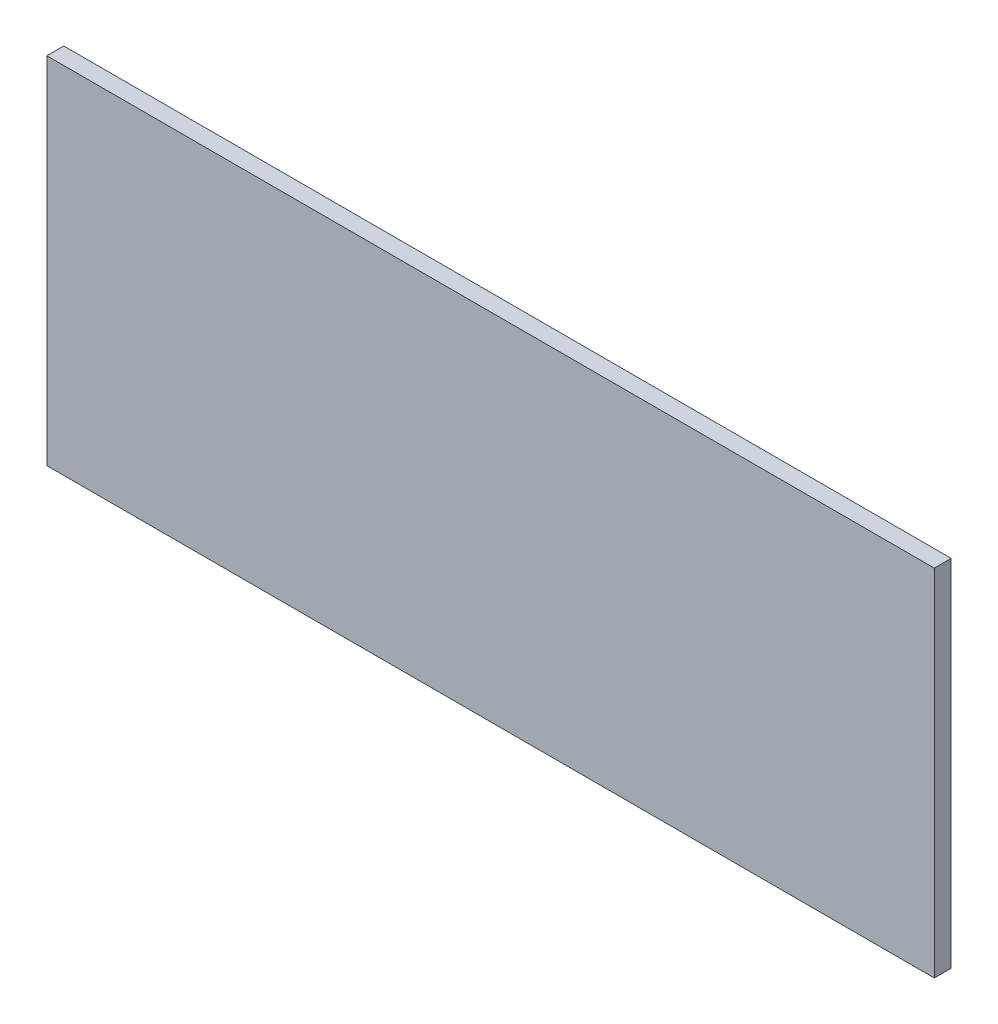
SolidWorks part; units mm, degrees
ref_plane "Alzado" through (0, 0, 0) normal (0, 0, 1) x (1, 0, 0)
ref_plane "Planta" through (0, 0, 0) normal (0, 1, 0) x (1, 0, 0)
ref_plane "Vista lateral" through (0, 0, 0) normal (1, 0, 0) x (0, 0, -1)
sketch "Croquis3" plane through (0, 0, 0) normal (0, 0, 1) x (1, 0, 0)
  line L2 (-90.5016, 84) -> (119.4984, 84)
  line L3 (-90.5016, 84) -> (-90.5016, 0)
  line L4 (-90.5016, 0) -> (119.4984, 0)
  line L5 (119.4984, 84) -> (119.4984, 0)
  dimension "D1" = 84
  dimension "D2" = 210
extrude "Saliente-Extruir2" add sketch "Croquis3" against normal blind 4
